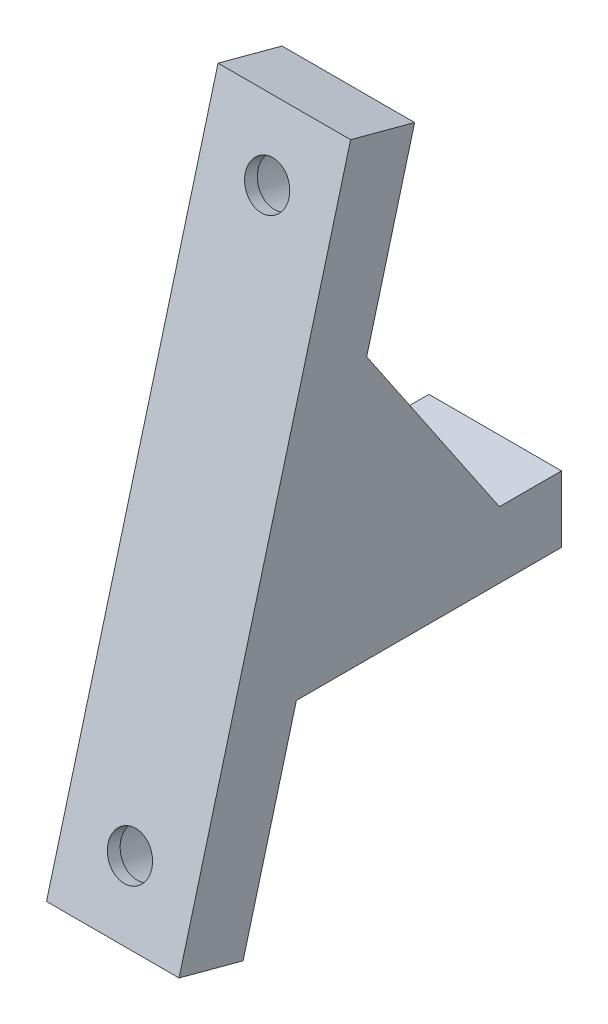
SolidWorks part; units mm, degrees
ref_plane "前视基准面" through (0, 0, 0) normal (0, 0, 1) x (1, 0, 0)
ref_plane "上视基准面" through (0, 0, 0) normal (0, 1, 0) x (1, 0, 0)
ref_plane "右视基准面" through (0, 0, 0) normal (1, 0, 0) x (0, 0, -1)
sketch "草图1" plane through (0, 0, 0) normal (1, 0, 0) x (0, 0, -1)
  line L0 (0, 0) -> (12.941, 48.2963)
  line L1 (12.941, 48.2963) -> (17.7706, 47.0022)
  line L2 (17.7706, 47.0022) -> (14.1551, 33.5091)
  line L3 (24.1639, 18.7059) -> (28.8489, 18.7059)
  line L4 (28.8489, 18.7059) -> (28.8489, 13.7059)
  line L5 (28.8489, 13.7059) -> (8.8489, 13.7059)
  line L8 (4.8296, -1.2941) -> (8.8489, 13.7059)
  line L9 (4.8296, -1.2941) -> (8.8489, 13.7059)
  line L10 (0, 0) -> (4.8296, -1.2941)
  line L11 (14.1551, 33.5091) -> (24.1639, 18.7059)
  dimension "D1" = 75
  dimension "D2" = 5
  dimension "D3" = 5
  dimension "D4" = 5
  dimension "D5" = 20
  dimension "D6" = 50
  dimension "D7" = 15
extrude "凸台-拉伸2" add sketch "草图1" along normal blind 10 contours L0 L10 L8 L5 L4 L3 L2 L1
sketch "草图3" plane through (0, -1.2941, -4.8296) normal (0, -0.2588, -0.9659) x (-1, 0, 0)
  line L0 (-10, 0) -> (0, 0) construction
  line L1 (-10, 0) -> (-10, 15.5291) construction
  circle A0 centre (-5, 45) radius 1.65
  circle A1 centre (-5, 5) radius 1.65
  dimension "D1" = 3.3
  dimension "D3" = 5
  dimension "D4" = 5
  dimension "D2" = 40
extrude "切除-拉伸2" cut sketch "草图3" against normal blind 10
sketch "草图5" plane through (0, 18.7059, 0) normal (0, 1, 0) x (1, 0, 0)
  line L0 (10, 24.1639) -> (10, 28.8489) construction
  line L1 (10, 28.8489) -> (0, 28.8489) construction
  circle A0 centre (5, 23.8489) radius 1.65
  dimension "D1" = 3.3
  dimension "D2" = 5
  dimension "D3" = 5
extrude "切除-拉伸3" cut sketch "草图5" against normal blind 9 and the other way blind 10
sketch "草图6" plane through (0, 18.7059, 0) normal (0, 1, 0) x (1, 0, 0)
  circle A0 centre (5, 23.8489) radius 3
  dimension "D1" = 6
extrude "切除-拉伸4" cut sketch "草图6" along normal blind 8
sketch "草图7" plane through (0, -1.2941, -4.8296) normal (0, -0.2588, -0.9659) x (-1, 0, 0)
  circle A0 centre (-5, 45) radius 2.25
  circle A1 centre (-5, 5) radius 2.25
  dimension "D1" = 4.5
extrude "切除-拉伸5" cut sketch "草图7" against normal blind 4
